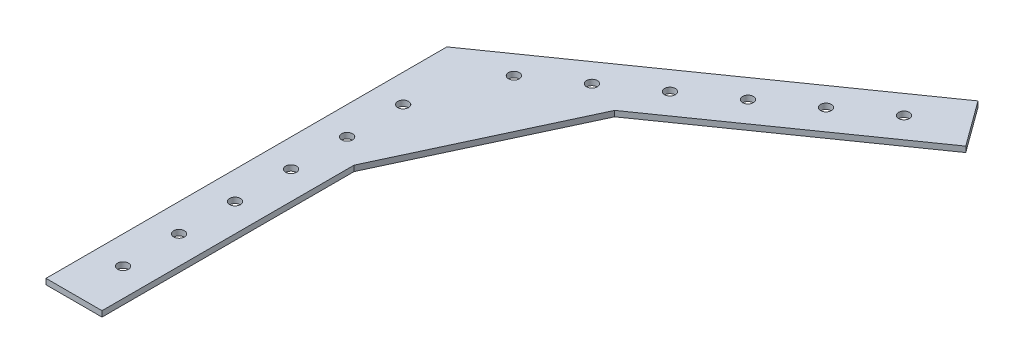
SolidWorks part; units mm, degrees
material "6061-T6 (SS)"
ref_plane "Front Plane" through (0, 0, 0) normal (0, 0, 1) x (1, 0, 0)
ref_plane "Top Plane" through (0, 0, 0) normal (0, 1, 0) x (1, 0, 0)
ref_plane "Right Plane" through (0, 0, 0) normal (1, 0, 0) x (0, 0, -1)
sketch "Sketch1" plane through (0, 0, 0) normal (0, 1, 0) x (1, 0, 0)
  line L0 (-49.1325, -114.0724) -> (-23.7325, -114.0724)
  line L1 (-23.7325, -114.0724) -> (-23.7325, 0.2276)
  line L2 (-23.7325, 0.2276) -> (13.8383, 80.7984)
  line L3 (13.8383, 80.7984) -> (107.4674, 146.3582)
  line L4 (92.4976, 166.8781) -> (107.4674, 146.3582)
  line L5 (-49.1325, -114.0724) -> (-49.1325, 67.7076)
  line L6 (-49.1325, 67.7076) -> (92.4976, 166.8781)
  dimension "D1" = 25.4
  dimension "D2" = 114.3
  dimension "D3" = 150
  dimension "D4" = 88.9
  dimension "D5" = 114.3
  dimension "D6" = 155
  dimension "D7" = 25.4
  dimension "D8" = 150
extrude "Boss-Extrude1" add sketch "Sketch1" along normal mid plane 2.54 contours L2 L3 L4 L6 L5 L0 L1
sketch "Sketch2" plane through (0, 1.27, 0) normal (0, 1, 0) x (1, 0, 0)
  line L0 (-49.1325, -114.0724) -> (-23.7325, -114.0724) construction
  line L4 (-23.7325, -114.0724) -> (-23.7325, 0.2276) construction
  point P0 (-36.4325, -91.8474)
  point P7 (-36.4325, -66.4474)
  point P8 (-36.4325, -41.0474)
  point P9 (-36.4325, -15.6474)
  point P10 (-36.4325, 9.7526)
  point P11 (-36.4325, 35.1526)
  dimension "D1" = 22.225
  dimension "D2" = 12.7
  dimension "D3" = 6
sketch "Sketch6" plane through (0, 1.27, 0) normal (0, 1, 0) x (1, 0, 0)
  line L0 (92.4976, 166.8781) -> (107.4674, 146.3582) construction
  line L1 (-49.1325, 67.7076) -> (92.4976, 166.8781) construction
  point P0 (81.4136, 144.4055)
  point P1 (99.9825, 156.6181)
  point P8 (60.6071, 129.8367)
  point P9 (39.8007, 115.2679)
  point P10 (18.9942, 100.699)
  point P11 (-1.8123, 86.1302)
  point P12 (-22.6187, 71.5613)
  dimension "D1" = 22.225
  dimension "D2" = 12.0509
  dimension "D3" = 6
hole_wizard "#10 (0.1935) Diameter Hole2" positions "Sketch8" profile "Sketch7" hole size "#10" standard "ANSI Inch"
sketch "Sketch8" plane through (0, 1.27, 0) normal (0, 1, 0) x (1, 0, 0)
  point P0 (81.4136, 144.4055)
  point P3 (60.6071, 129.8367)
  point P6 (39.8007, 115.2679)
  point P9 (18.9942, 100.699)
  point P12 (-1.8123, 86.1302)
  point P15 (-22.6187, 71.5613)
  point P18 (-36.4325, 35.1526)
  point P21 (-36.4325, 9.7526)
  point P24 (-36.4325, -15.6474)
  point P27 (-36.4325, -41.0474)
  point P30 (-36.4325, -66.4474)
  point P33 (-36.4325, -91.8474)
sketch "Sketch7" plane through (81.4136, 1.27, -144.4055) normal (1, 0, 0) x (0, 0, 1)
  line L0 (0, 0) -> (0, 52.2766)
  line L1 (0, 52.2766) -> (2.4574, 50.8)
  line L2 (2.4574, 50.8) -> (2.4574, 0)
  line L5 (2.4574, 0) -> (0, 0)
  line L10 (0, 52.2766) -> (-2.4575, 50.8) construction
  line L11 (0, -6.35) -> (0, 107.95) construction
  dimension "Hole Dia." = 4.9149
  dimension "Hole Depth" = 50.8
  dimension "Drill Angle" = 118
